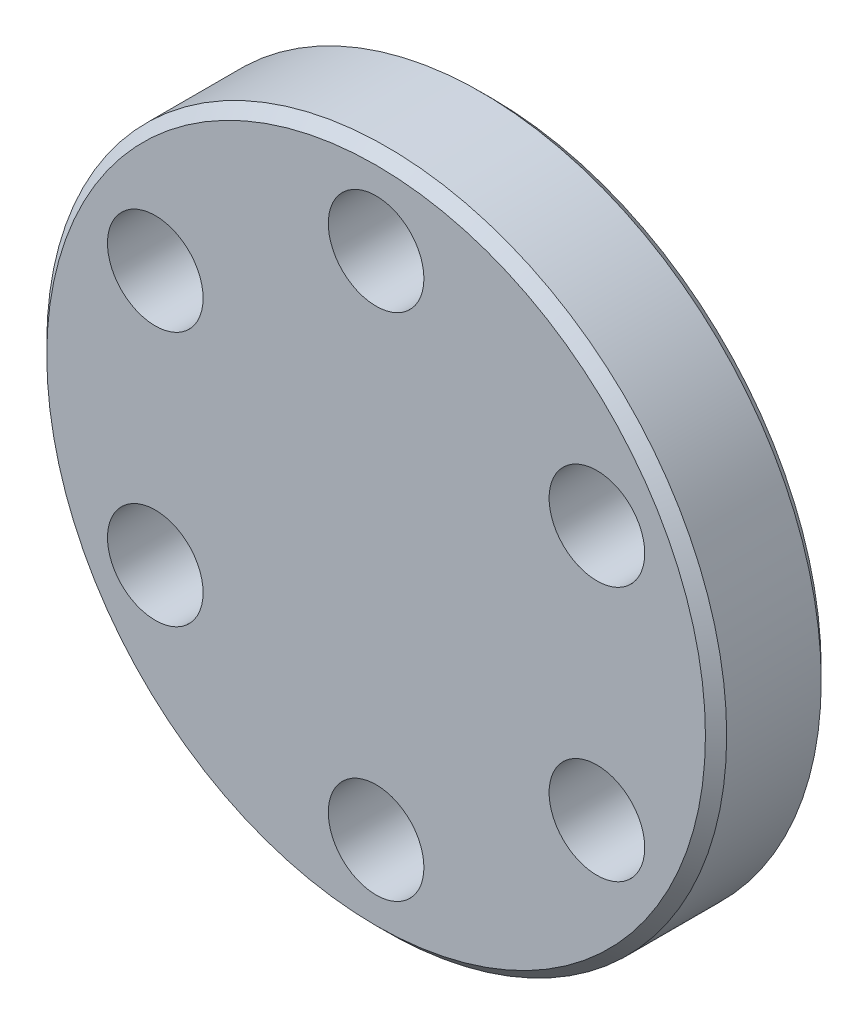
SolidWorks part; units mm, degrees
ref_plane "Ebene vorne" through (0, 0, 0) normal (0, 0, 1) x (1, 0, 0)
ref_plane "Ebene oben" through (0, 0, 0) normal (0, 1, 0) x (1, 0, 0)
ref_plane "Ebene rechts" through (0, 0, 0) normal (1, 0, 0) x (0, 0, -1)
sketch "Skizze1" plane through (0, 0, 0) normal (0, 0, 1) x (1, 0, 0)
  circle A0 centre (0, 0) radius 16
  dimension "D1" = 32
extrude "Aufsatz-Linear austragen1" add sketch "Skizze1" along normal mid plane 5.45
hole_wizard "Durchgangsloch für M41" positions "Skizze2" profile "Skizze4" hole size "M4" standard "DIN" end condition through all
sketch "Skizze2" plane through (0, 0, 2.725) normal (0, 0, 1) x (1, 0, 0)
  circle A1 centre (0, 0) radius 12
  point P12 (0, 12)
  point P20 (10.3923, 6)
  point P21 (10.3923, -6)
  point P22 (0, -12)
  point P23 (-10.3923, -6)
  point P24 (-10.3923, 6)
  dimension "D1" = 24
  dimension "D2" = 6
sketch "Skizze4" plane through (-10.3923, 6, 2.725) normal (1, 0, 0) x (0, -1, 0)
  line L0 (0, 0) -> (0, 5.45)
  line L1 (0, 5.45) -> (2.25, 5.45)
  line L2 (2.25, 5.45) -> (2.25, 0)
  line L5 (2.25, 0) -> (0, 0)
  line L11 (0, -6.35) -> (0, 107.95) construction
  dimension "Bohrerdurchmesser" = 4.5
  dimension "Bohrungstiefe" = 5.45
chamfer "Fase1" distance 0.5 angle 45 2 edges at (16, 0, -2.725) (16, 0, 2.725)
